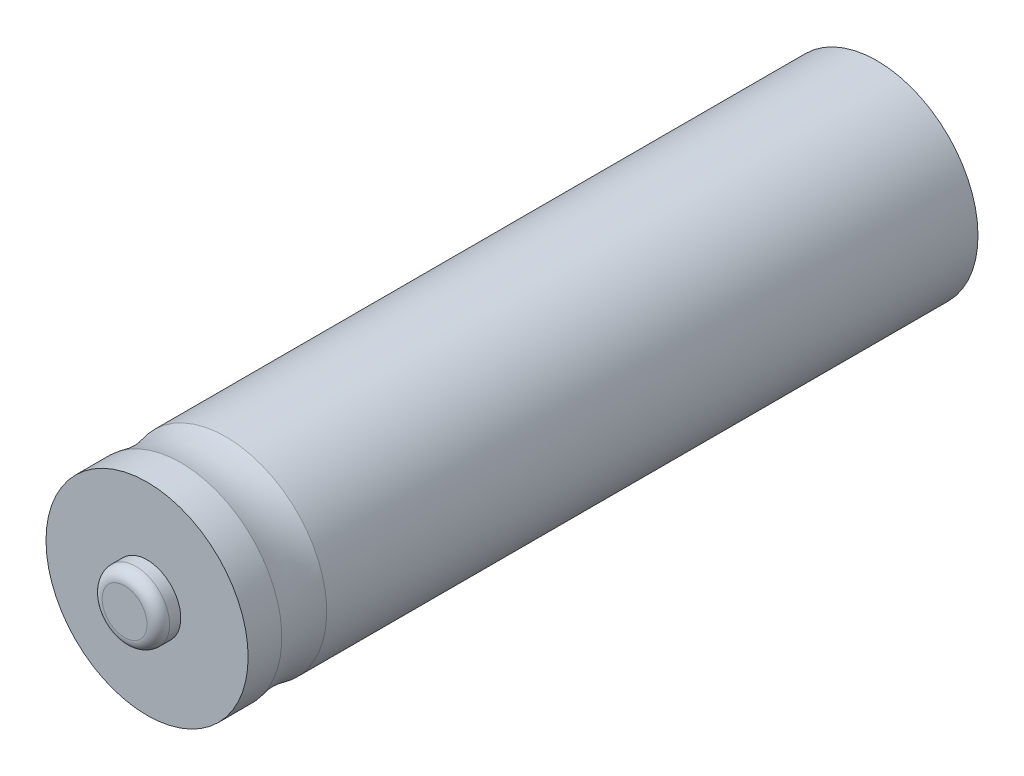
SolidWorks part; units mm, degrees
ref_plane "Plano frontal" through (0, 0, 0) normal (0, 0, 1) x (1, 0, 0)
ref_plane "Plano superior" through (0, 0, 0) normal (0, 1, 0) x (1, 0, 0)
ref_plane "Plano direito" through (0, 0, 0) normal (1, 0, 0) x (0, 0, -1)
sketch "Esboço1" plane through (0, 0, 0) normal (0, 0, 1) x (1, 0, 0)
  circle A0 centre (0, 0) radius 9
  dimension "D1" = 18
extrude "Ressalto-extrusão1" add sketch "Esboço1" along normal mid plane 65
sketch "Esboço2" plane through (0, 0, 32.5) normal (0, 0, 1) x (1, 0, 0)
  circle A0 centre (0, 0) radius 3
  dimension "D1" = 6
extrude "Ressalto-extrusão2" add sketch "Esboço2" along normal blind 2
fillet "Filete1" radius 1 1 edges at (3, 0, 34.5)
sketch "Esboço3" plane through (0, 0, 0) normal (1, 0, 0) x (0, 0, -1)
  line L4 (-34.5, 0) -> (-40.2176, 0) construction
  line L5 (-34.5, 2) -> (-34.5, -2) construction
  line L6 (-29.5, 9) -> (-25.5, 9)
  arc A0 (-29.5, 9) -> (-25.5, 9) centre (-27.5, 16.5444) ccw
  point P1 (0, 0)
revolve "Corte-Revolução1" cut sketch "Esboço3" angle 360 about L4
sketch "Esboço4" plane through (0, 0, -32.5) normal (0, 0, -1) x (-1, 0, 0)
  circle A0 centre (0, 0) radius 5.5
  dimension "D1" = 11
extrude "Ressalto-extrusão3" add sketch "Esboço4" along normal blind 0.4
